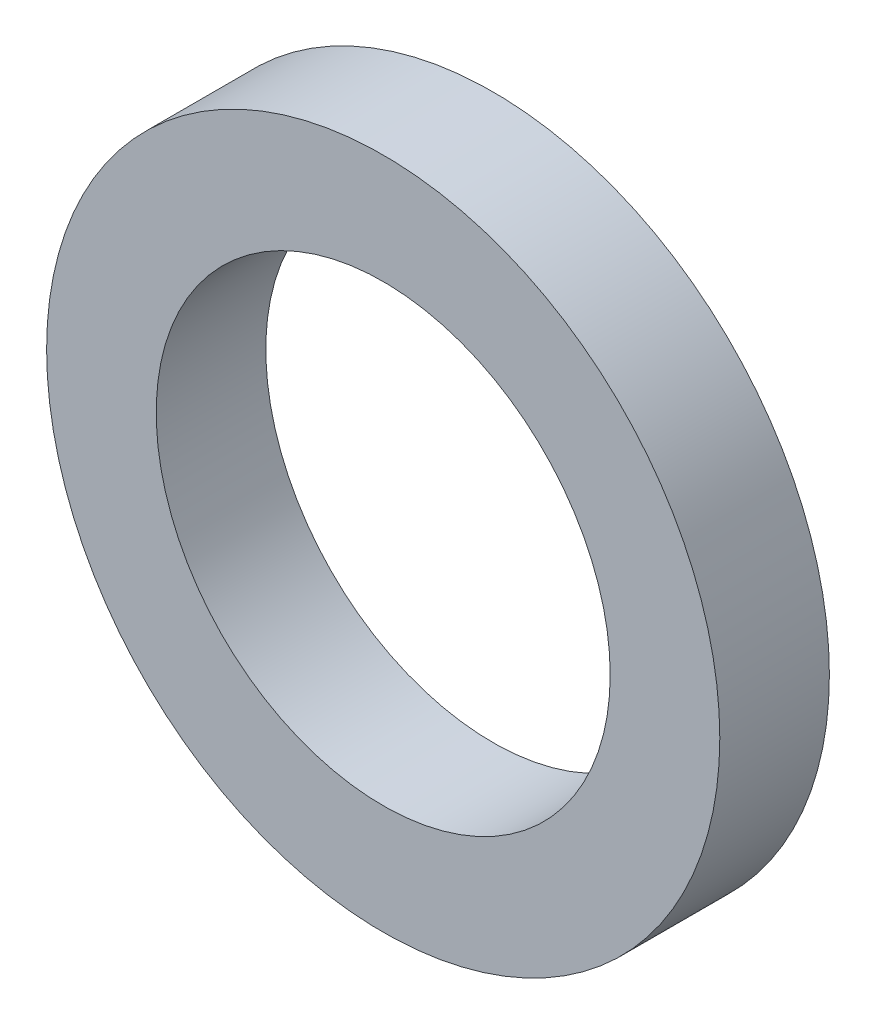
SolidWorks part; units mm, degrees
ref_plane "Front Plane" through (0, 0, 0) normal (0, 0, 1) x (1, 0, 0)
ref_plane "Top Plane" through (0, 0, 0) normal (0, 1, 0) x (1, 0, 0)
ref_plane "Right Plane" through (0, 0, 0) normal (1, 0, 0) x (0, 0, -1)
sketch "Sketch1" plane through (0, 0, 0) normal (0, 0, 1) x (1, 0, 0)
  circle A0 centre (0, 0) radius 14.5
  circle A1 centre (0, 0) radius 21.5
  dimension "D1" = 29
  dimension "D2" = 43
extrude "Boss-Extrude1" add sketch "Sketch1" along normal blind 7
